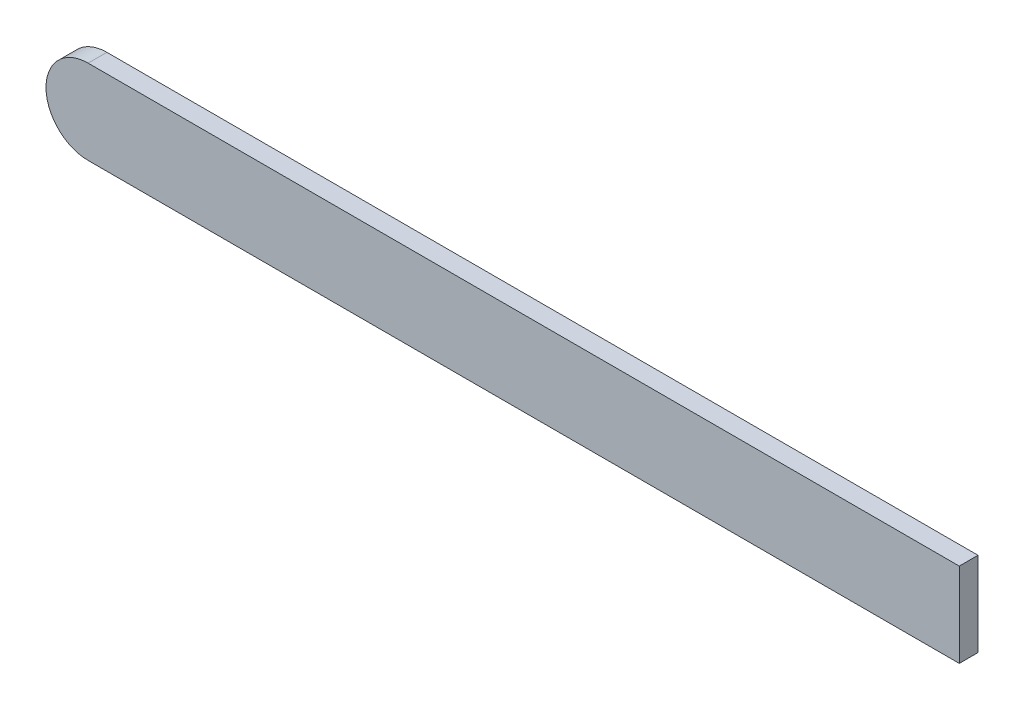
SolidWorks part; units mm, degrees
ref_plane "Front Plane" through (0, 0, 0) normal (0, 0, 1) x (1, 0, 0)
ref_plane "Top Plane" through (0, 0, 0) normal (0, 1, 0) x (1, 0, 0)
ref_plane "Right Plane" through (0, 0, 0) normal (1, 0, 0) x (0, 0, -1)
sketch "Sketch1" plane through (0, 0, 0) normal (0, 0, 1) x (1, 0, 0)
  line L0 (-44.45, 0) -> (50.0074, 0) construction
  line L1 (-44.45, 4.7625) -> (53.975, 4.7625)
  line L2 (-44.45, -4.7625) -> (53.975, -4.7625)
  line L3 (53.975, 4.7625) -> (53.975, -4.7625)
  arc A0 (-44.45, 4.7625) -> (-44.45, -4.7625) centre (-44.45, 0) ccw
  point P3 (0, 0)
  dimension "D2" = 4.7625
  dimension "D1" = 98.425
  dimension "D3" = 4.7625
  dimension "D4" = 53.975
  dimension "D5" = 9.525
extrude "Boss-Extrude1" add sketch "Sketch1" along normal blind 2.1167
